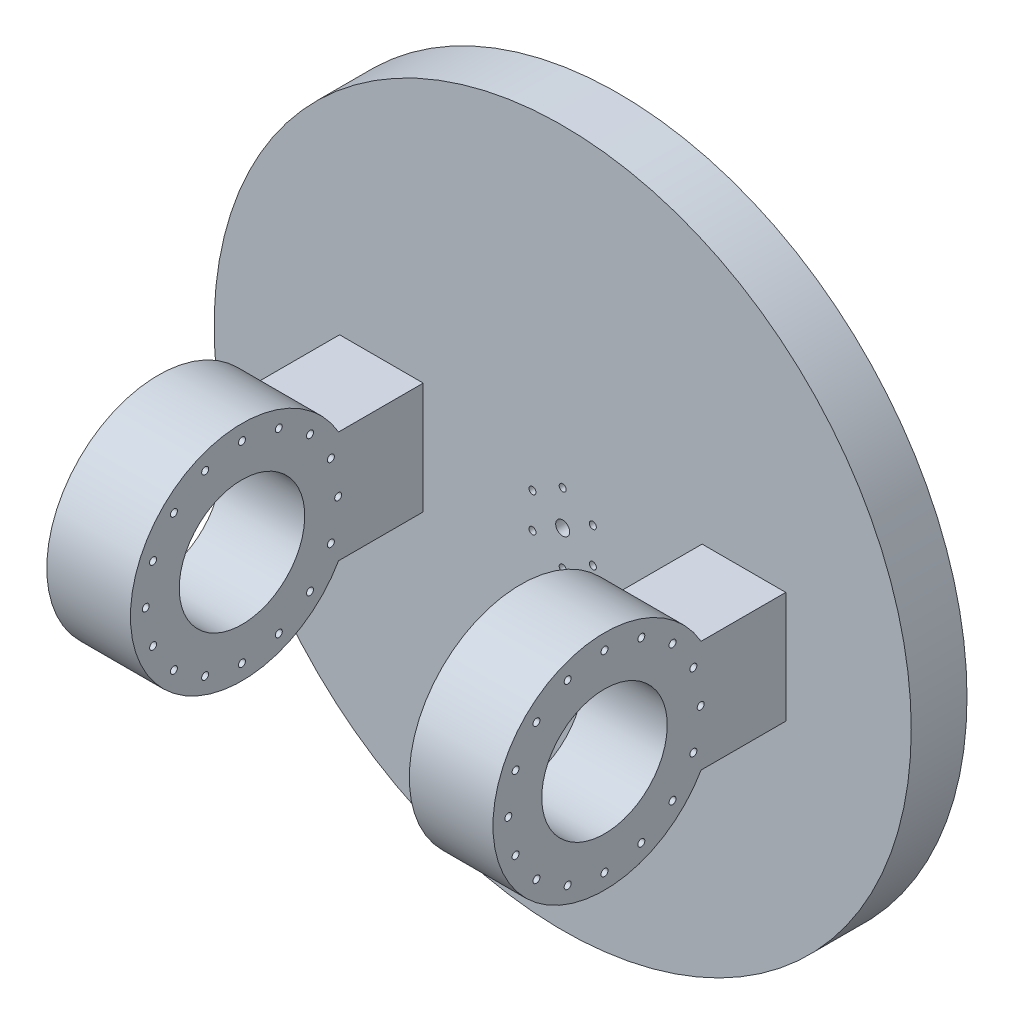
SolidWorks part; units mm, degrees
ref_plane "前视基准面" through (0, 0, 0) normal (0, 0, 1) x (1, 0, 0)
ref_plane "上视基准面" through (0, 0, 0) normal (0, 1, 0) x (1, 0, 0)
ref_plane "右视基准面" through (0, 0, 0) normal (1, 0, 0) x (0, 0, -1)
sketch "草图1" plane through (0, 0, 0) normal (0, 0, 1) x (1, 0, 0)
  circle A0 centre (0, 0) radius 16
  dimension "D1" = 32
extrude "凸台-拉伸1" add sketch "草图1" along normal blind 10
sketch "草图2" plane through (0, 0, 0) normal (0, 0, -1) x (-1, 0, 0)
  line L0 (0, 12.5) -> (0, -11.1794) construction
  circle A0 centre (0, 0) radius 12.5 construction
  circle A1 centre (0, 12.5) radius 1.25
  circle A2 centre (10.8253, 6.25) radius 1.25
  circle A3 centre (10.8253, -6.25) radius 1.25
  circle A4 centre (0, -12.5) radius 1.25
  circle A5 centre (-10.8253, -6.25) radius 1.25
  circle A6 centre (-10.8253, 6.25) radius 1.25
  point P18 (0, 0)
  dimension "D1" = 25
  dimension "D2" = 2.5
  dimension "D3" = 6
extrude "凸台-拉伸2" add sketch "草图2" along normal blind 10.2
sketch "草图3" plane through (0, 0, 10) normal (0, 0, 1) x (1, 0, 0)
  circle A0 centre (0, 0) radius 125
  dimension "D1" = 250
extrude "凸台-拉伸3" add sketch "草图3" against normal blind 20
sketch "草图4" plane through (0, 0, 10) normal (0, 0, 1) x (1, 0, 0)
  line L0 (0, 125) -> (0, -56.1206) construction
  line L1 (-125, 0) -> (74.6169, 0) construction
  line L2 (80, 20) -> (50, 20)
  line L3 (-80, -20) -> (-50, -20)
  line L4 (-80, -20) -> (-80, 20)
  line L5 (-80, 20) -> (-50, 20)
  line L6 (-50, -20) -> (-50, 20)
  line L7 (50, -20) -> (50, 20)
  line L8 (80, -20) -> (50, -20)
  line L9 (80, -20) -> (80, 20)
  circle A0 centre (0, 0) radius 125 construction
  dimension "D1" = 100
  dimension "D2" = 30
  dimension "D3" = 40
extrude "凸台-拉伸4" add sketch "草图4" along normal blind 41.07
sketch "草图7" plane through (0, 0, 0) normal (0, 0, -1) x (-1, 0, 0)
  circle A0 centre (0, 0) radius 4.1
  dimension "D1" = 8.2
extrude "切除-拉伸1" cut sketch "草图7" against normal blind 4
sketch "草图16" plane through (-80, 0, 0) normal (-1, 0, 0) x (0, 0, 1)
  line L1 (10, 0) -> (119.4189, 0) construction
  line L2 (10, 20) -> (10, -20) construction
  circle A0 centre (75, 0) radius 40
  dimension "D1" = 80
  dimension "D2" = 65
extrude "凸台-拉伸10" add sketch "草图16" against normal up to surface (30 mm away) up to face at (-50, 0, 30.535)
sketch "草图17" plane through (80, 0, 0) normal (1, 0, 0) x (0, 0, -1)
  line L3 (-40.359, -20) -> (-10, -20)
  line L4 (-10, -20) -> (-10, 20)
  line L5 (-10, 20) -> (-51.07, 20)
  line L6 (-51.07, 20) -> (-51.07, -20)
  line L7 (-51.07, -20) -> (-10, -20)
  line L9 (-40.359, 20) -> (-51.07, 20)
  line L10 (-51.07, 20) -> (-51.07, -20)
  line L11 (-51.07, -20) -> (-40.359, -20)
  line L12 (-10, 20) -> (-40.359, 20)
  line L13 (-10, -20) -> (-10, 20)
  arc A1 (-40.359, 20) -> (-40.359, -20) centre (-75, 0) ccw
  arc A2 (-40.359, 20) -> (-40.359, -20) centre (-75, 0) ccw
  dimension "D1" = 0
  dimension "D2" = 0
extrude "凸台-拉伸11" add sketch "草图17" against normal up to surface (30 mm away) up to face at (50, 0, 30.535)
sketch "草图18" plane through (-80, 0, 0) normal (-1, 0, 0) x (0, 0, 1)
  line L1 (115, 0) -> (-22.5647, 0) construction
  line L2 (75, 40) -> (75, -66.8567) construction
  arc A0 (40.359, -20) -> (40.359, 20) centre (75, 0) ccw construction
  circle A1 centre (75, 0) radius 34.5 construction
  circle A2 centre (109.5, 0) radius 1.25
  circle A3 centre (106.8738, -13.2026) radius 1.25
  circle A4 centre (99.3952, -24.3952) radius 1.25
  circle A5 centre (88.2026, -31.8738) radius 1.25
  circle A6 centre (75, -34.5) radius 1.25
  circle A7 centre (61.7974, -31.8738) radius 1.25
  circle A8 centre (50.6048, -24.3952) radius 1.25
  circle A9 centre (43.1262, -13.2026) radius 1.25
  circle A10 centre (40.5, 0) radius 1.25
  circle A11 centre (43.1262, 13.2026) radius 1.25
  circle A12 centre (50.6048, 24.3952) radius 1.25
  circle A13 centre (61.7974, 31.8738) radius 1.25
  circle A14 centre (75, 34.5) radius 1.25
  circle A15 centre (88.2026, 31.8738) radius 1.25
  circle A16 centre (99.3952, 24.3952) radius 1.25
  circle A17 centre (106.8738, 13.2026) radius 1.25
  point P46 (75, 0)
  dimension "D1" = 69
  dimension "D2" = 2.5
  dimension "D3" = 16
extrude "切除-拉伸6" cut sketch "草图18" against normal through all both and the other way through all
sketch "草图19" plane through (80, 0, 0) normal (1, 0, 0) x (0, 0, -1)
  line L0 (-75, 40) -> (-75, -51.898) construction
  line L1 (-115, 0) -> (22.01, 0) construction
  arc A0 (-40.359, 20) -> (-40.359, -20) centre (-75, 0) ccw construction
  circle A1 centre (-75, 0) radius 22.5
  dimension "D1" = 45
extrude "切除-拉伸7" cut sketch "草图19" against normal blind 180
sketch "草图20" plane through (0, 0, -10) normal (0, 0, -1) x (-1, 0, 0)
  circle A0 centre (0, 12.5) radius 1.25
  circle A1 centre (10.8253, 6.25) radius 1.25
  circle A2 centre (10.8253, -6.25) radius 1.25
  circle A3 centre (0, -12.5) radius 1.25
  circle A4 centre (-10.8253, -6.25) radius 1.25
  circle A5 centre (-10.8253, 6.25) radius 1.25
  point P15 (0, 0)
  dimension "D1" = 6
extrude "切除-拉伸8" cut sketch "草图20" against normal through all both and the other way through all
sketch "草图21" plane through (0, 0, 10) normal (0, 0, 1) x (1, 0, 0)
  circle A0 centre (0, 0) radius 2.5
  dimension "D1" = 5
extrude "切除-拉伸9" cut sketch "草图21" against normal through all both and the other way through all
